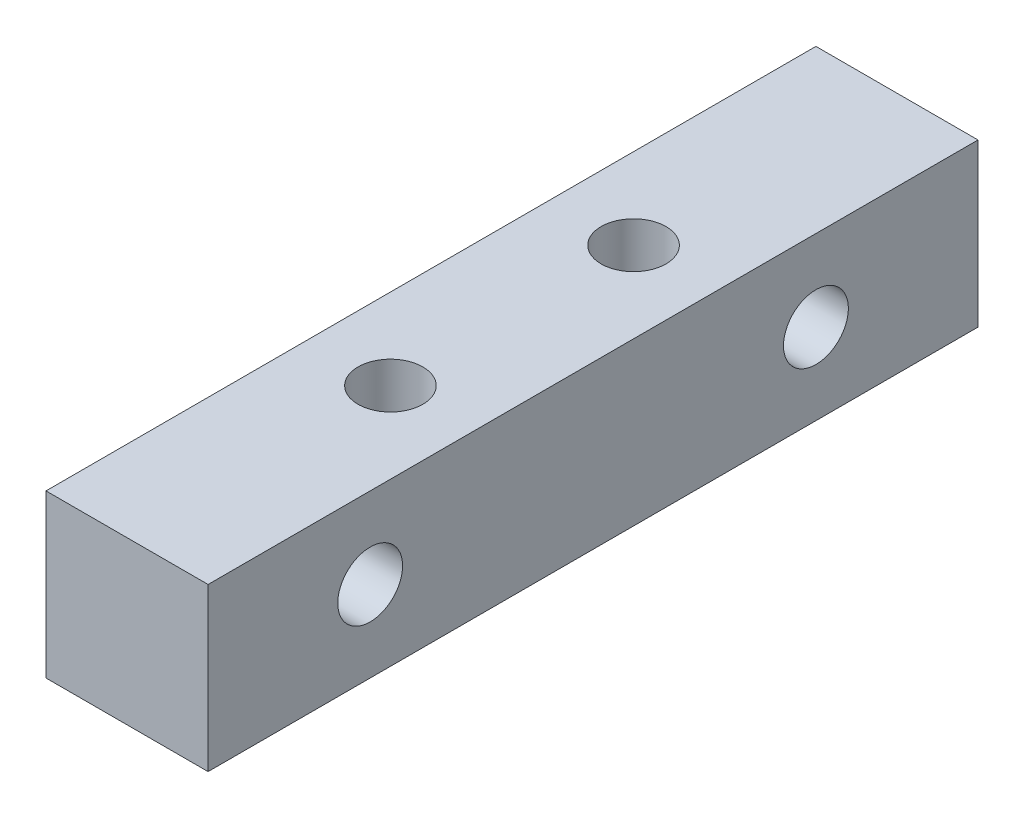
SolidWorks part; units mm, degrees
ref_plane "前视基准面" through (0, 0, 0) normal (0, 0, 1) x (1, 0, 0)
ref_plane "上视基准面" through (0, 0, 0) normal (0, 1, 0) x (1, 0, 0)
ref_plane "右视基准面" through (0, 0, 0) normal (1, 0, 0) x (0, 0, -1)
sketch "草图1" plane through (0, 0, 0) normal (0, 0, 1) x (1, 0, 0)
  line L1 (-4, -4) -> (4, -4)
  line L2 (-4, -4) -> (-4, 4)
  line L3 (-4, 4) -> (4, 4)
  line L4 (4, -4) -> (4, 4)
  line L5 (-4, -4) -> (4, 4) construction
  line L6 (-4, 4) -> (4, -4) construction
  point P0 (0, 0)
  dimension "D1" = 8
  dimension "D2" = 8
extrude "凸台-拉伸1" add sketch "草图1" along normal blind 38
sketch "草图2" plane through (4, 0, 0) normal (1, 0, 0) x (0, 0, -1)
  line L0 (-38, 0) -> (49962, 0) construction
  line L1 (-38, -4) -> (-38, 4) construction
  line L2 (-19, 4) -> (-19, -49996) construction
  line L3 (-38, 4) -> (0, 4) construction
  circle A0 centre (-30, 0) radius 1.6
  circle A1 centre (-8, 0) radius 1.6
  point P4 (-38, 0)
  point P9 (-19, 4)
  dimension "D1" = 3.2
  dimension "D2" = 22
sketch "草图3" plane through (0, 4, 0) normal (0, 1, 0) x (1, 0, 0)
  line L0 (0, 0) -> (0, -50000) construction
  line L1 (4, 0) -> (-4, 0) construction
  line L2 (-4, -19) -> (49996, -19) construction
  line L3 (-4, -38) -> (-4, 0) construction
  circle A0 centre (0, -13) radius 1.6
  circle A1 centre (0, -25) radius 1.6
  point P4 (0, 0)
  point P9 (-4, -19)
  dimension "D1" = 3.2
  dimension "D2" = 12
extrude "切除-拉伸1" cut sketch "草图3" against normal through all
extrude "切除-拉伸2" cut sketch "草图2" against normal through all
equation "\"3。2\"=3.52993"
